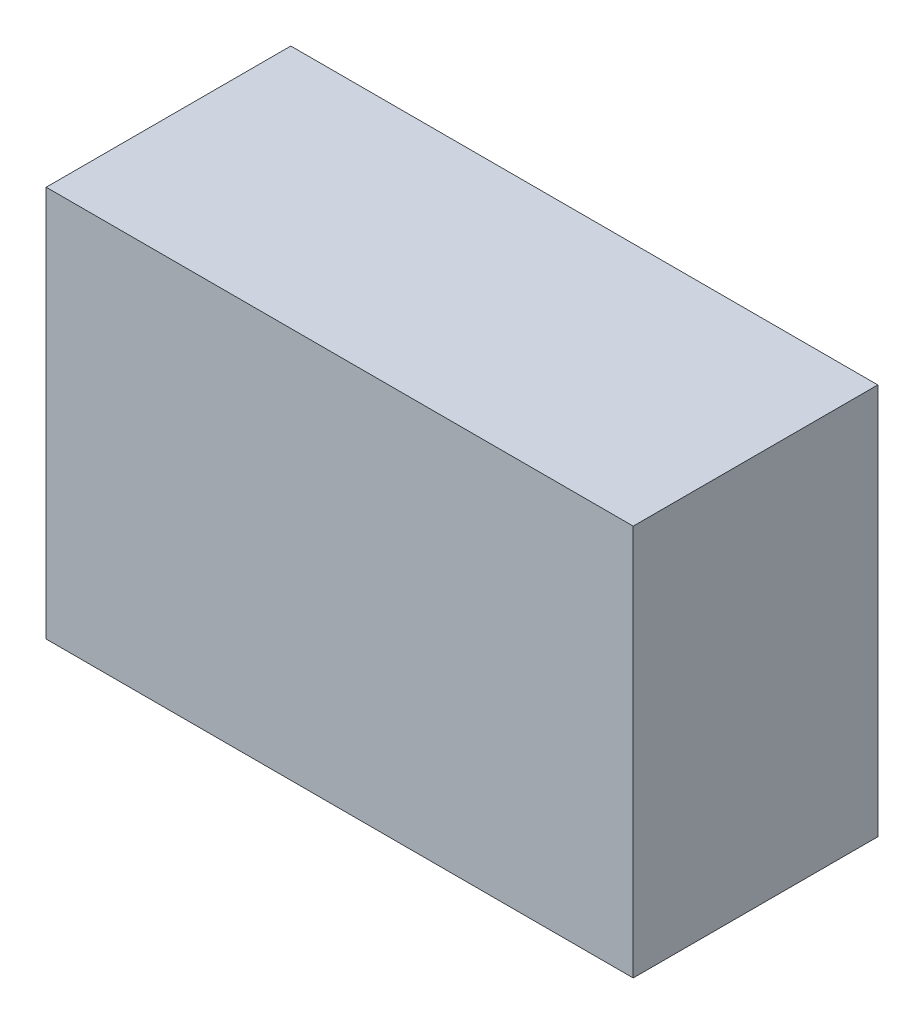
SolidWorks part; units mm, degrees
ref_plane "Plan de face" through (0, 0, 0) normal (0, 0, 1) x (1, 0, 0)
ref_plane "Plan de dessus" through (0, 0, 0) normal (0, 1, 0) x (1, 0, 0)
ref_plane "Plan de droite" through (0, 0, 0) normal (1, 0, 0) x (0, 0, -1)
sketch "Esquisse1" plane through (0, 0, 0) normal (0, 0, 1) x (1, 0, 0)
  line L1 (0, 0) -> (-60, 0)
  line L2 (0, 0) -> (0, 40)
  line L3 (0, 40) -> (-60, 40)
  line L4 (-60, 0) -> (-60, 40)
  dimension "D1" = 40
  dimension "D2" = 60
extrude "Extrusion1" add sketch "Esquisse1" along normal blind 25
